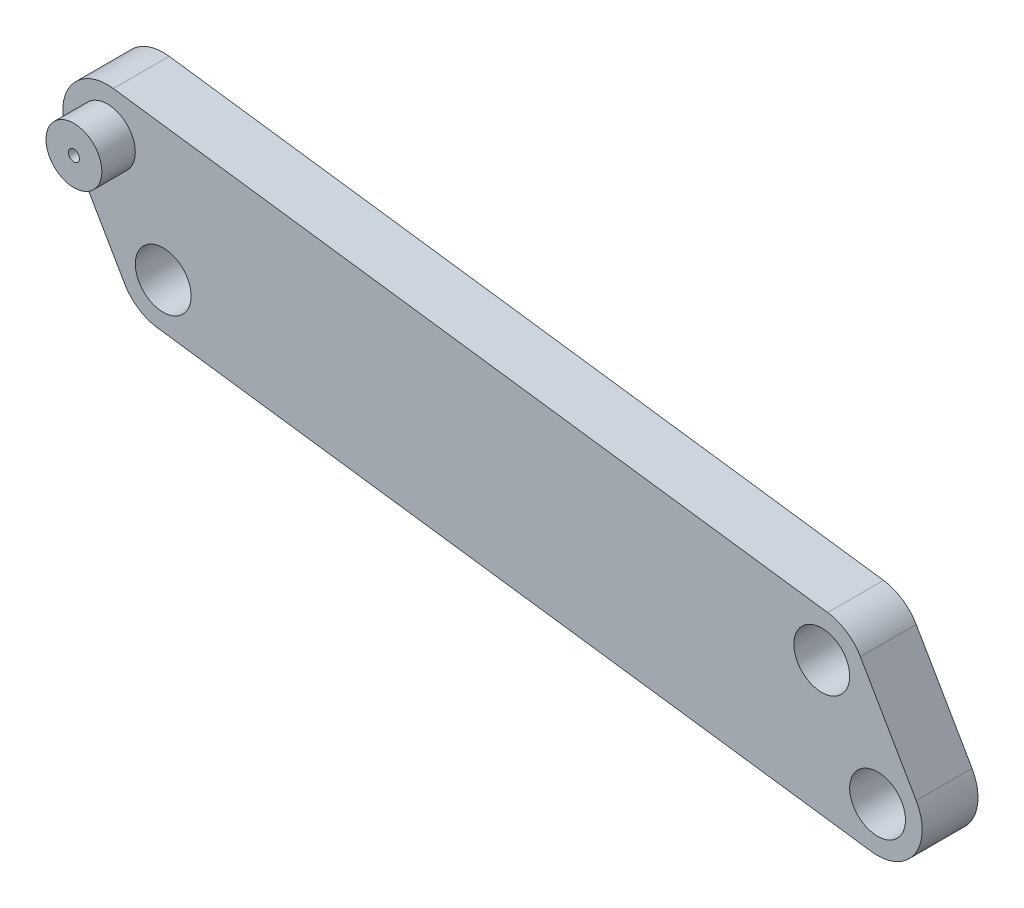
SolidWorks part; units mm, degrees
ref_plane "Front Plane" through (0, 0, 0) normal (0, 0, 1) x (1, 0, 0)
ref_plane "Top Plane" through (0, 0, 0) normal (0, 1, 0) x (1, 0, 0)
ref_plane "Right Plane" through (0, 0, 0) normal (1, 0, 0) x (0, 0, -1)
sketch "Sketch1" plane through (0, 0, 0) normal (0, 0, 1) x (1, 0, 0)
  line L0 (0, 0) -> (-59, 0)
  line L1 (-59, 0) -> (-64, 8.6603)
  line L2 (0, 0) -> (5, -8.6603)
  dimension "D1" = 59
  dimension "D2" = 10
  dimension "D3" = 10
  dimension "D4" = 120
  dimension "D5" = 120
sketch "Sketch2" plane through (0, 0, 0) normal (0, 0, 1) x (1, 0, 0)
  line L0 (-63.4636, 12.6241) -> (0.5364, 3.9639)
  line L1 (3.4641, 2) -> (8.4641, -6.6603)
  line L2 (4.4636, -12.6241) -> (-59.5364, -3.9639)
  line L3 (-62.4641, -2) -> (-67.4641, 6.6603)
  circle A0 centre (-59, 0) radius 2.5
  circle A1 centre (-64, 8.6603) radius 2.5
  arc A2 (-63.4636, 12.6241) -> (-67.4641, 6.6603) centre (-64, 8.6603) ccw
  arc A3 (-62.4641, -2) -> (-59.5364, -3.9639) centre (-59, 0) ccw
  circle A4 centre (0, 0) radius 2.5
  circle A5 centre (5, -8.6603) radius 2.5
  arc A6 (3.4641, 2) -> (0.5364, 3.9639) centre (0, 0) ccw
  arc A7 (4.4636, -12.6241) -> (8.4641, -6.6603) centre (5, -8.6603) ccw
  dimension "D1" = 5
  dimension "D2" = 5
  dimension "D3" = 5
  dimension "D4" = 5
  dimension "D5" = 8
  dimension "D6" = 8
  dimension "D7" = 8
  dimension "D8" = 8
extrude "Boss-Extrude1" add sketch "Sketch2" along normal blind 5
sketch "Sketch4" plane through (0, 0, 0) normal (0, 0, -1) x (-1, 0, 0)
  circle A0 centre (64, 8.6603) radius 2.5
  circle A1 centre (64, 8.6603) radius 0.5
  dimension "D1" = 1
  dimension "D2" = 5
extrude "Boss-Extrude3" add sketch "Sketch4" against normal blind 8
